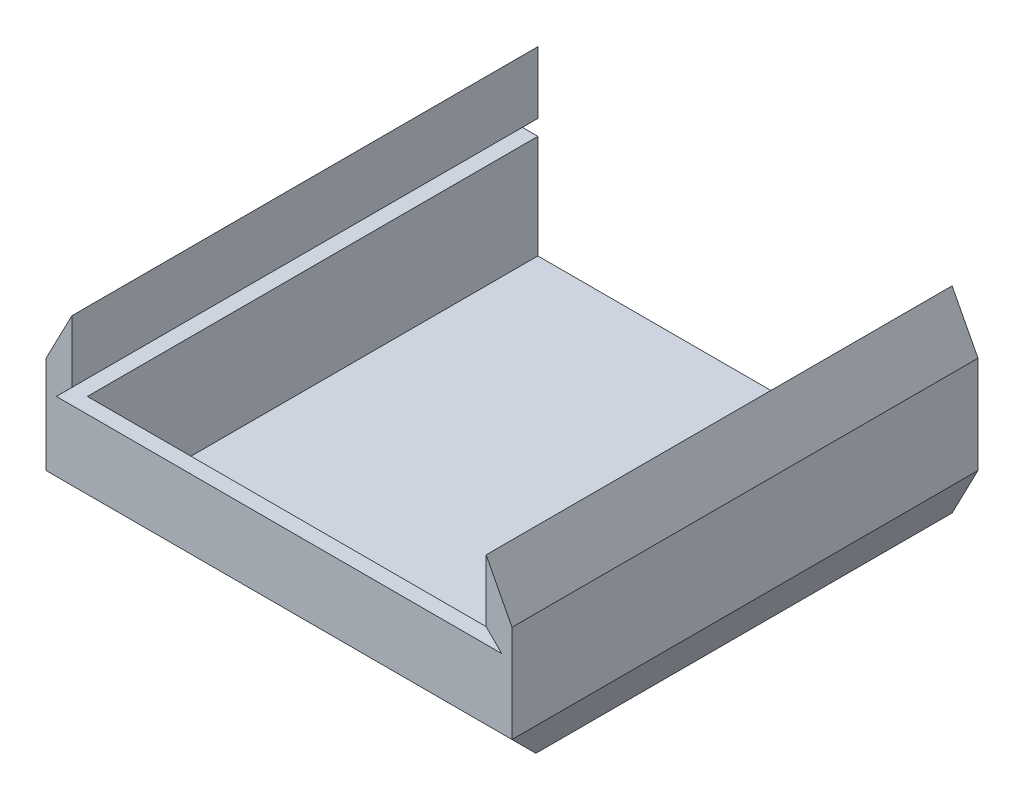
SolidWorks part; units mm, degrees
ref_plane "Front Plane" through (0, 0, 0) normal (0, 0, 1) x (1, 0, 0)
ref_plane "Top Plane" through (0, 0, 0) normal (0, 1, 0) x (1, 0, 0)
ref_plane "Right Plane" through (0, 0, 0) normal (1, 0, 0) x (0, 0, -1)
sketch "Sketch1" plane through (0, 0, 0) normal (0, 1, 0) x (1, 0, 0)
  line L1 (0, 0) -> (80, 0)
  line L2 (0, 0) -> (0, 90)
  line L3 (0, 90) -> (80, 90)
  line L4 (80, 0) -> (80, 90)
  dimension "D1" = 80
  dimension "D2" = 90
extrude "Boss-Extrude1 (Base)" add sketch "Sketch1" along normal blind 3
sketch "Sketch4" plane through (0, 0, 0) normal (0, 0, 1) x (1, 0, 0)
  line L0 (-3, 23) -> (0, 26)
  line L1 (0, 26) -> (0, 23)
  line L2 (0, 23) -> (-3, 23)
  line L3 (0, 3) -> (80, 3) construction
  line L6 (0, 3) -> (0, 0) construction
  line L7 (40, 28.9013) -> (40, -8.4397) construction
  line L8 (80, 3) -> (80, 0) construction
  line L9 (80, 23) -> (83, 23)
  line L10 (80, 26) -> (80, 23)
  line L11 (83, 23) -> (80, 26)
  dimension "D1" = 20
  dimension "D2" = 3
  dimension "D3" = 3
  dimension "D4" = 40
sketch "Sketch5" plane through (0, 0, 0) normal (0, 0, 1) x (1, 0, 0)
  line L6 (40, -8.4397) -> (40, 28.9013) construction
  line L11 (-5, 28.3909) -> (0, 38)
  line L12 (0, 38) -> (0, 0)
  line L13 (0, 0) -> (-5, 9.6091)
  line L14 (-5, 9.6091) -> (-5, 28.3909)
  line L16 (0, 3) -> (80, 3) construction
  line L17 (85, 9.6091) -> (85, 28.3909)
  line L18 (80, 0) -> (85, 9.6091)
  line L19 (80, 38) -> (80, 0)
  line L20 (85, 28.3909) -> (80, 38)
  dimension "D1" = 5
  dimension "D2" = 35
extrude "Boss-Extrude4 (Side Walls)" add sketch "Sketch5" against normal through all
extrude "Cut-Extrude2 (Guide Holes)" cut sketch "Sketch4" against normal through all
sketch "Sketch15" plane through (0, 0, 0) normal (0, 0, 1) x (1, 0, 0)
  line L1 (0, 23) -> (80, 23)
  line L2 (0, 23) -> (0, 3)
  line L3 (0, 3) -> (80, 3)
  line L4 (80, 23) -> (80, 3)
extrude "Boss-Extrude9 (Front Wall)" add sketch "Sketch15" against normal blind 3
chamfer "Chamfer5 (Front Chamfer)" distance 9.61 angle 45 1 edges at (40, 0, 0)
chamfer "Chamfer6 (Front Chamfer Cleanup)" distance 5 angle 45 1 edges at (40, 3, -3)
